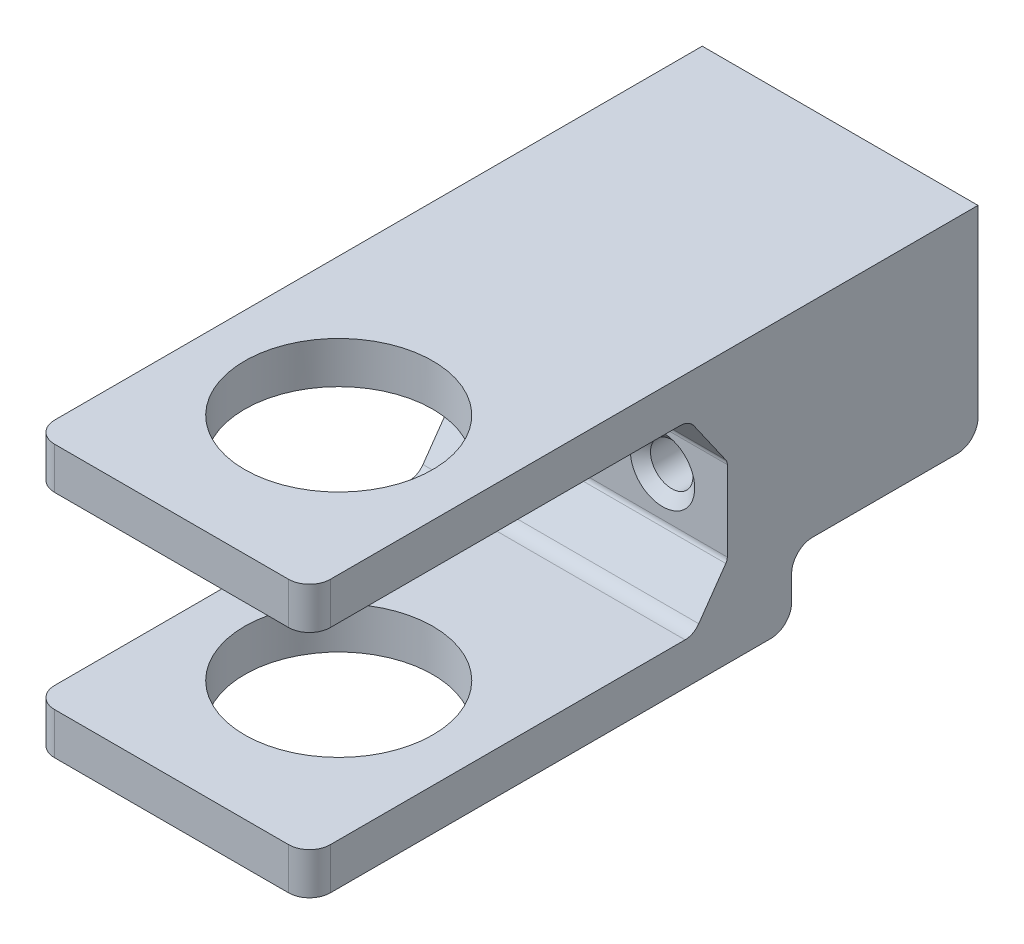
SolidWorks part; units mm, degrees
ref_plane "Front Plane" through (0, 0, 0) normal (0, 0, 1) x (1, 0, 0)
ref_plane "Top Plane" through (0, 0, 0) normal (0, 1, 0) x (1, 0, 0)
ref_plane "Right Plane" through (0, 0, 0) normal (1, 0, 0) x (0, 0, -1)
sketch "Sketch1" plane through (0, 0, 0) normal (0, 1, 0) x (1, 0, 0)
  line L1 (-20.955, -50.8) -> (20.955, -50.8)
  line L2 (-20.955, -50.8) -> (-20.955, 50.8)
  line L3 (-20.955, 50.8) -> (20.955, 50.8)
  line L4 (20.955, -50.8) -> (20.955, 50.8)
  line L5 (-20.955, -50.8) -> (20.955, 50.8) construction
  line L6 (-20.955, 50.8) -> (20.955, -50.8) construction
  point P0 (0, 0)
  dimension "D1" = 41.91
  dimension "D2" = 101.6
extrude "Boss-Extrude1" add sketch "Sketch1" along normal blind 41.275
sketch "Sketch13" plane through (-20.955, 0, 0) normal (-1, 0, 0) x (0, 0, 1)
  line L0 (-12.7, 26.6024) -> (-6.8725, 34.925)
  line L1 (-6.8725, 34.925) -> (50.8, 34.925)
  line L2 (-12.7, 26.6024) -> (-12.7, 13.6323)
  line L3 (-7.6009, 6.35) -> (50.8, 6.35)
  line L4 (-50.8, 0) -> (50.8, 0)
  line L5 (50.8, 0) -> (50.8, 41.275)
  line L6 (50.8, 41.275) -> (-50.8, 41.275)
  line L7 (-50.8, 41.275) -> (-50.8, 0)
  line L8 (-50.8, 0) -> (50.8, 0)
  line L9 (50.8, 0) -> (50.8, 41.275)
  line L10 (50.8, 41.275) -> (-50.8, 41.275)
  line L11 (-50.8, 41.275) -> (-50.8, 0)
  line L12 (50.8, 34.925) -> (50.8, 6.35)
  line L13 (-12.7, 13.6323) -> (-7.6009, 6.35)
  point P2 (-11.5709, 6.35)
  point P6 (-19.685, 9.8373)
  line M11 (50.8, 0) -> (50.8, 41.275)
  dimension "D2" = 6.35
  dimension "D3" = 38.1
  dimension "D4" = 6.35
  dimension "D5" = 10.16
  dimension "D6" = 125
  dimension "D7" = 8.89
  dimension "D8" = 57.6725
  dimension "D9" = 125
  dimension "D1" = 0
extrude "Cut-Extrude6" cut sketch "Sketch13" against normal through all contours L2 L13 L3 L1 L0 M11
sketch "Sketch3" plane through (0, 41.275, 0) normal (0, 1, 0) x (1, 0, 0)
  line L1 (20.955, 50.8) -> (-20.955, 50.8) construction
  line L3 (2.7496, -20.6375) -> (-2.7496, -20.6375)
  line L4 (-2.7496, -20.6375) -> (-5.4993, -25.4)
  line L5 (-5.4993, -25.4) -> (-2.7496, -30.1625)
  line L6 (-2.7496, -30.1625) -> (2.7496, -30.1625)
  line L7 (2.7496, -30.1625) -> (5.4993, -25.4)
  line L8 (5.4993, -25.4) -> (2.7496, -20.6375)
  circle A0 centre (0, -25.4) radius 50.8
  circle A1 centre (0, -25.4) radius 4.7625 construction
  circle A2 centre (0, -25.4) radius 14.3002
  dimension "D1" = 101.6
  dimension "D2" = 25.4
  dimension "D3" = 9.525
  dimension "D4" = 28.6004
extrude "Cut-Extrude2" cut sketch "Sketch3" against normal through all contours L7 L8 L3 L4 L5 L6 | A2 L8 L7 L6 L5 L4 L3
sketch "Sketch17" plane through (-20.955, 0, 0) normal (-1, 0, 0) x (0, 0, 1)
  line L11 (-50.8, 41.275) -> (-50.8, 0) construction
  line L16 (-50.8, 0) -> (-22.479, 0)
  line L17 (-50.8, 0) -> (-50.8, 10.16)
  line L18 (-50.8, 10.16) -> (-22.479, 10.16)
  line L19 (-22.479, 0) -> (-22.479, 10.16)
  line L20 (-50.8, 0) -> (50.8, 0) construction
  dimension "D1" = 28.321
  dimension "D2" = 10.16
extrude "Cut-Extrude7" cut sketch "Sketch17" against normal through all
sketch "Sketch4" plane through (0, 0, -50.8) normal (0, 0, -1) x (-1, 0, 0)
  line L0 (-20.955, 20.6375) -> (20.955, 20.6375) construction
  line L1 (-20.955, 41.275) -> (-20.955, 10.16) construction
  line L3 (11.1125, 20.6375) -> (-11.1125, 20.6375) construction
  line L4 (-20.955, 41.275) -> (20.955, 41.275) construction
  circle A0 centre (11.1125, 20.6375) radius 3.2258
  circle A1 centre (-11.1125, 20.6375) radius 3.2258
  point P2 (0, 0)
  point P5 (0, 0)
  point P10 (0, 20.6375)
  point P11 (0, 0)
  point P12 (0, 20.6375)
  point P13 (-20.955, 20.6375)
  dimension "D1" = 6.4516
  dimension "D2" = 22.225
  dimension "D3" = 20.6375
  dimension "D4" = 41.91
extrude "Cut-Extrude3" cut sketch "Sketch4" against normal through all
fillet "Fillet2" radius 3.175 7 edges at (-20.955, 3.175, 50.8) (20.955, 3.175, 50.8) (-20.955, 38.1, 50.8) (20.955, 38.1, 50.8) (0, 10.16, -50.8) (0, 0, -22.479) (0, 10.16, -22.479)
hole_wizard "CSK for #10 Flat Head Machine Screw (100)4" positions "Sketch14" profile "Sketch15" countersink size "#10" standard "ANSI Inch"
sketch "Sketch14" plane through (0, 0, -12.7) normal (0, 0, 1) x (1, 0, 0)
  point P0 (-11.1125, 20.6375)
  point P3 (11.1125, 20.6375)
sketch "Sketch15" plane through (-11.1125, 20.6375, -12.7) normal (1, 0, 0) x (0, -1, 0)
  line L0 (0, 0) -> (0, 39.7864)
  line L1 (0, 39.7864) -> (2.8067, 38.1)
  line L2 (2.8067, 38.1) -> (2.8067, 1.7477)
  line L3 (2.8067, 1.7477) -> (4.8895, 0)
  line L5 (4.8895, 0) -> (0, 0)
  line L6 (-2.8067, 1.7477) -> (-4.8895, 0) construction
  line L10 (0, 39.7864) -> (-2.8067, 38.1) construction
  line L11 (0, -6.35) -> (0, 107.95) construction
  dimension "Hole Dia." = 5.6134
  dimension "Hole Depth" = 38.1
  dimension "Near C'Sink Dia." = 9.779
  dimension "Near C'Sink Angle" = 100
  dimension "Drill Angle" = 118
fillet "Fillet3" radius 2.54 2 edges at (0, 6.35, -7.6009) (0, 34.925, -6.8725)
fillet "Fillet4" radius 1.27 2 edges at (0, 13.6323, -12.7) (0, 26.6024, -12.7)
